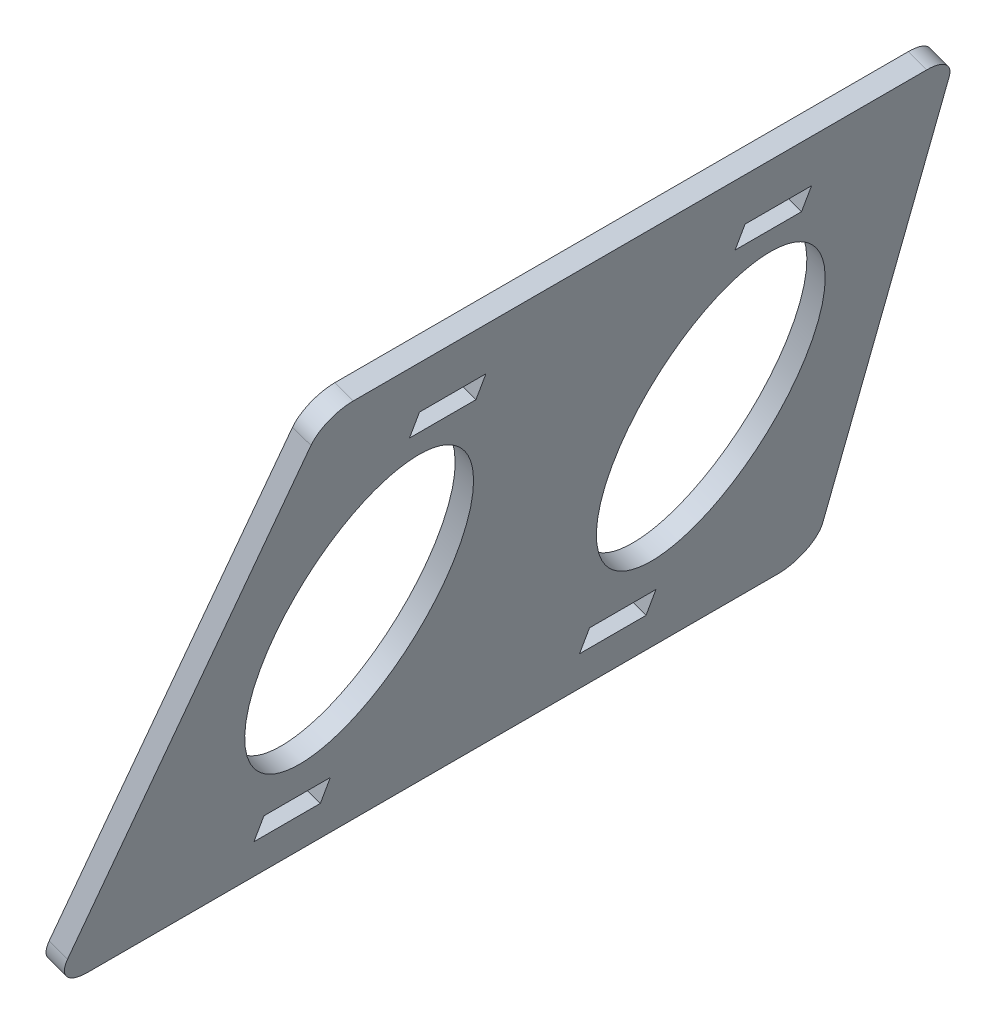
SolidWorks part; units mm, degrees
material "Blue Acrylic"
ref_plane "Front Plane" through (0, 0, 0) normal (0, 0, 1) x (1, 0, 0)
ref_plane "Top Plane" through (0, 0, 0) normal (0, 1, 0) x (1, 0, 0)
ref_plane "Right Plane" through (0, 0, 0) normal (1, 0, 0) x (0, 0, -1)
sketch "Sketch1" plane through (0, 0, 0) normal (0, 0, 1) x (1, 0, 0)
  line L0 (-70.4528, 211.3413) -> (-95.4318, 142.7123) construction
  line L1 (-66.6592, 221.7643) -> (-69.4783, 222.7904)
  line L2 (-66.6592, 221.7643) -> (-98.4785, 134.3414)
  line L3 (-98.4785, 134.3414) -> (-101.2976, 135.3675)
  line L4 (-69.4783, 222.7904) -> (-101.2976, 135.3675)
  line L5 (-98.6243, 142.7123) -> (-74.7373, 208.3413) construction
  line L8 (-63.8401, 220.7382) -> (-66.6592, 221.7643) construction
  line L9 (-95.6594, 133.3154) -> (-98.4785, 134.3414) construction
extrude "Boss-Extrude1" add sketch "Sketch1" along normal mid plane 116
sketch "Sketch2" plane through (-132.9543, 48.3914, 0) normal (-0.9397, 0.342, 0) x (0, 0, 1)
  line L12 (57.9711, 98.0951) -> (49, 181.1286)
  line L13 (-53, 92.558) -> (53, 92.558)
  line L14 (-49, 181.1286) -> (-57.9711, 98.0951)
  line L15 (44.0289, 185.5915) -> (-44.0289, 185.5915)
  line L16 (0, 56.3816) -> (0, 234.4107) construction
  line L17 (0, 56.3816) -> (0, 234.4107) construction
  line L18 (57.9711, 98.0951) -> (49, 181.1286)
  line L20 (-53, 92.558) -> (53, 92.558)
  line L21 (-49, 181.1286) -> (-57.9711, 98.0951)
  line L22 (44.0289, 185.5915) -> (-44.0289, 185.5915)
  arc A8 (49, 181.1286) -> (44.0289, 185.5915) centre (44.0289, 180.5915) ccw
  arc A9 (53, 92.558) -> (57.9711, 98.0951) centre (53, 97.558) ccw
  arc A10 (-57.9711, 98.0951) -> (-53, 92.558) centre (-53, 97.558) ccw
  arc A11 (-44.0289, 185.5915) -> (-49, 181.1286) centre (-44.0289, 180.5915) ccw
  arc A14 (49, 181.1286) -> (44.0289, 185.5915) centre (44.0289, 180.5915) ccw
  arc A15 (53, 92.558) -> (57.9711, 98.0951) centre (53, 97.558) ccw
  arc A16 (-57.9711, 98.0951) -> (-53, 92.558) centre (-53, 97.558) ccw
  arc A17 (-44.0289, 185.5915) -> (-49, 181.1286) centre (-44.0289, 180.5915) ccw
  dimension "D2" = 0
extrude "tab and slot contour" cut sketch "Sketch2" against normal up to next (3 mm away) flip side to cut
sketch "Sketch4" plane through (-132.9543, 48.3914, 0) normal (-0.9397, 0.342, 0) x (0, 0, 1)
  line L0 (-25, 174.4996) -> (-25, 170.2151) construction
  line L1 (-25, 104.6586) -> (-25, 100.3742) construction
  line L2 (-25, 172.7724) -> (-25, 168.9687) construction
  line L3 (-30, 174.4996) -> (-20, 174.4996) construction
  line L4 (-30, 174.4996) -> (-30, 170.2151) construction
  line L5 (-30, 170.2151) -> (-20, 170.2151) construction
  line L6 (-20, 174.4996) -> (-20, 170.2151) construction
  line L7 (-30, 104.6586) -> (-20, 104.6586) construction
  line L8 (-30, 104.6586) -> (-30, 100.3742) construction
  line L9 (-30, 100.3742) -> (-20, 100.3742) construction
  line L10 (-20, 104.6586) -> (-20, 100.3742) construction
  line L11 (-25, 102.9315) -> (-25, 99.0765) construction
  line L12 (-30, 172.3574) -> (-20, 172.3574) construction
  line L13 (0, 0) -> (0, 204.5119) construction
  line L14 (-30.1, 175.6915) -> (-30.1, 171.207) construction
  line L15 (-30.1, 174.5996) -> (-19.9, 174.5996)
  line L16 (-30.1, 174.5996) -> (-30.1, 170.1151)
  line L17 (-30.1, 170.1151) -> (-19.9, 170.1151)
  line L18 (-19.9, 174.5996) -> (-19.9, 170.1151)
  line L19 (-30.1, 171.207) -> (-19.9, 171.207) construction
  line L20 (-30, 102.5164) -> (-20, 102.5164) construction
  line L21 (-30.1, 104.7586) -> (-19.9, 104.7586)
  line L22 (-30.1, 104.7586) -> (-30.1, 100.2742)
  line L23 (-30.1, 100.2742) -> (-19.9, 100.2742)
  line L24 (-19.9, 104.7586) -> (-19.9, 100.2742)
  line L25 (30.1, 174.5996) -> (30.1, 170.1151)
  line L26 (30.1, 174.5996) -> (19.9, 174.5996)
  line L27 (19.9, 174.5996) -> (19.9, 170.1151)
  line L28 (30.1, 170.1151) -> (19.9, 170.1151)
  line L29 (30.1, 104.7586) -> (30.1, 100.2742)
  line L30 (30.1, 104.7586) -> (19.9, 104.7586)
  line L31 (19.9, 104.7586) -> (19.9, 100.2742)
  line L32 (30.1, 100.2742) -> (19.9, 100.2742)
  dimension "D1" = 10
extrude "mounting tab slot" cut sketch "Sketch4" against normal up to next
sketch "Sketch3" plane through (-132.9543, 48.3914, 0) normal (-0.9397, 0.342, 0) x (0, 0, 1)
  line L0 (0, 0) -> (0, 225.0854) construction
  ellipse E0 centre (-27, 138.4369) end of major axis (-27, 111.6586) minor radius 15
  ellipse E1 centre (27, 138.4369) end of major axis (27, 111.6586) minor radius 15
  dimension "D1" = 53.5565
  dimension "D4" = 30
extrude "eye aperture" cut sketch "Sketch3" against normal up to next
